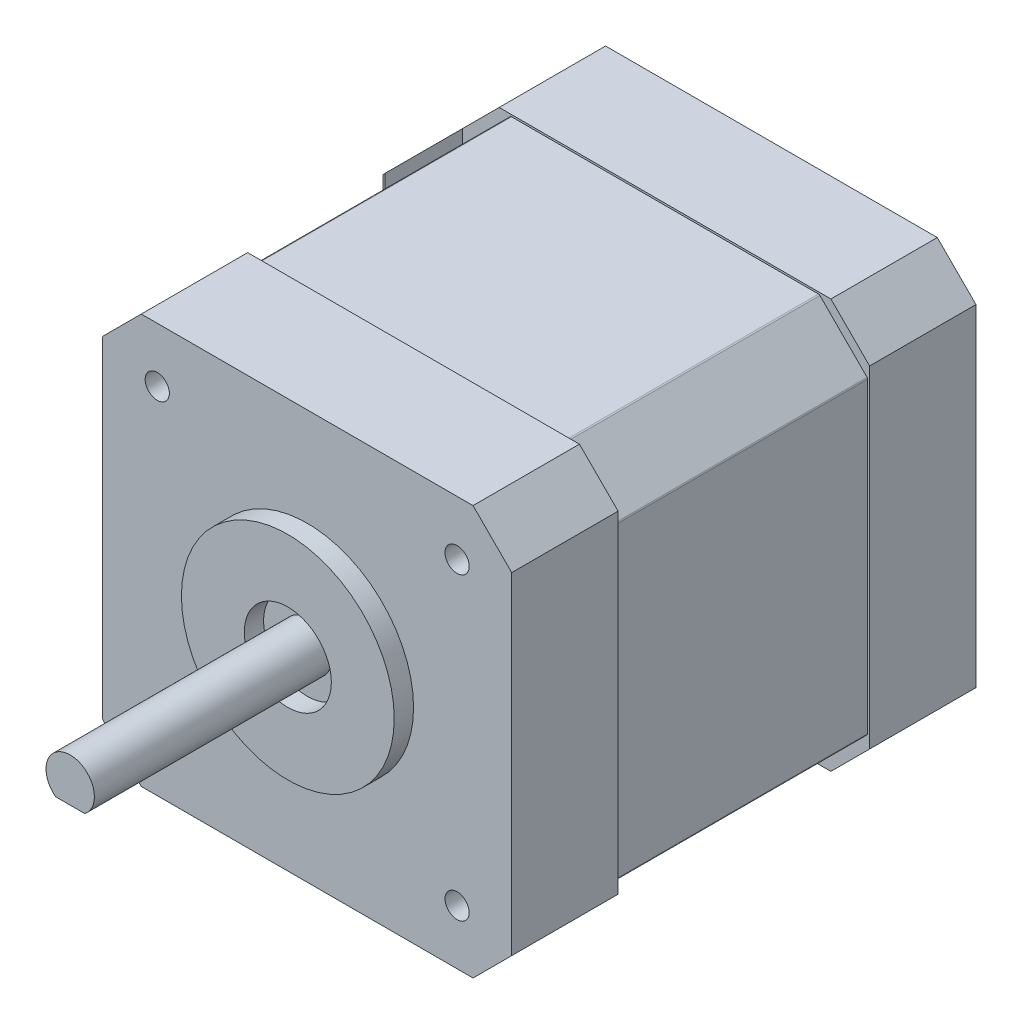
SolidWorks part; units mm, degrees
ref_plane "Plan de face" through (0, 0, 0) normal (0, 0, 1) x (1, 0, 0)
ref_plane "Plan de dessus" through (0, 0, 0) normal (0, 1, 0) x (1, 0, 0)
ref_plane "Plan de droite" through (0, 0, 0) normal (1, 0, 0) x (0, 0, -1)
ref_plane "Plan1" through (0, 0, -11) normal (0, 0, 1) x (1, 0, 0)
sketch "Esquisse1" plane through (0, 0, -11) normal (0, 0, 1) x (1, 0, 0)
  line L0 (20.95, 15.95) -> (15.95, 20.95)
  line L1 (15.95, 20.95) -> (-15.95, 20.95)
  line L2 (-15.95, 20.95) -> (-20.95, 15.95)
  line L3 (-20.95, 15.95) -> (-20.95, -15.95)
  line L4 (-20.95, -15.95) -> (-15.95, -20.95)
  line L5 (-15.95, -20.95) -> (15.95, -20.95)
  line L6 (15.95, -20.95) -> (20.95, -15.95)
  line L7 (20.95, -15.95) -> (20.95, 15.95)
extrude "Boss.-Extru.1" add sketch "Esquisse1" against normal blind 26
sketch "Esquisse2" plane through (0, 0, -37) normal (0, 0, -1) x (-1, 0, 0)
  line L0 (20.95, 21.15) -> (20.95, -21.15)
  line L1 (20.95, -21.15) -> (-21.15, -21.15)
  line L2 (-21.15, -21.15) -> (-21.15, 21.15)
  line L3 (-21.15, 21.15) -> (20.95, 21.15)
extrude "Boss.-Extru.2" add sketch "Esquisse2" along normal blind 11
sketch "Esquisse3" plane through (-20.95, 0, 0) normal (-1, 0, 0) x (0, 0, 1)
  line L0 (-40, -21.15) -> (-40, 21.15)
  line L1 (-40, 21.15) -> (-29, 21.15)
  line L2 (-29, 21.15) -> (-29, -21.15)
  line L3 (-29, -21.15) -> (-40, -21.15)
extrude "Boss.-Extru.3" add sketch "Esquisse3" along normal blind 0.2
ref_plane "Plan2" through (0, 0, -11) normal (0, 0, -1) x (-1, 0, 0)
sketch "Esquisse4" plane through (0, 0, -11) normal (0, 0, -1) x (-1, 0, 0)
  line L0 (-21.15, 21.15) -> (-21.15, -21.15)
  line L1 (-21.15, -21.15) -> (21.15, -21.15)
  line L2 (21.15, -21.15) -> (21.15, 21.15)
  line L3 (21.15, 21.15) -> (-21.15, 21.15)
extrude "Boss.-Extru.4" add sketch "Esquisse4" against normal blind 11
sketch "Esquisse5" plane through (0, 0, 0) normal (0, 0, 1) x (1, 0, 0)
  circle A0 centre (0, 0) radius 11
extrude "Boss.-Extru.5" add sketch "Esquisse5" along normal blind 2
hole_wizard "Diamètre du perçage Ø9.0 (9)1" positions "Esquisse7" profile "Esquisse6" hole size "Ø9.0" standard "Ansi Metric"
sketch "Esquisse7" plane through (0, 0, 2) normal (0, 0, 1) x (1, 0, 0)
  point P0 (0, 0)
sketch "Esquisse6" plane through (0, 0, 2) normal (1, 0, 0) x (0, -1, 0)
  line L0 (0, 0) -> (0, 2)
  line L1 (0, 2) -> (4.5, 2)
  line L2 (4.5, 2) -> (4.5, 0)
  line L5 (4.5, 0) -> (0, 0)
  line L10 (0, 2) -> (-4.5, 2) construction
  line L11 (0, -6.35) -> (0, 107.95) construction
  dimension "Diamètre du perçage" = 9
  dimension "Profondeur du perçage" = 2
  dimension "Angle de pointe" = 180
sketch "Esquisse8" plane through (0, 0, 0) normal (0, 0, 1) x (1, 0, 0)
  circle A0 centre (0, 0) radius 2.5
extrude "Boss.-Extru.6" add sketch "Esquisse8" along normal blind 24.5
sketch "Esquisse9" plane through (0, 0, 24.5) normal (0, 0, 1) x (1, 0, 0)
  line L0 (1.5, -2) -> (-1.5, -2)
  arc A0 (-1.5, -2) -> (1.5, -2) centre (0, 0) ccw
extrude "Enlèv. mat.-Extru.1" cut sketch "Esquisse9" against normal blind 15
hole_wizard "Diamètre du perçage Ø2.5 (2.5)1" positions "Esquisse11" profile "Esquisse10" hole size "Ø2.5" standard "Ansi Metric"
sketch "Esquisse11" plane through (0, 0, 0) normal (0, 0, 1) x (1, 0, 0)
  point P0 (-15.5, 15.5)
  point P1 (-15.5, -15.5)
  point P2 (15.5, -15.5)
  point P3 (15.5, 15.5)
sketch "Esquisse10" plane through (-15.5, 15.5, 0) normal (1, 0, 0) x (0, -1, 0)
  line L0 (0, 0) -> (0, 8.2511)
  line L1 (0, 8.2511) -> (1.25, 7.5)
  line L2 (1.25, 7.5) -> (1.25, 0)
  line L5 (1.25, 0) -> (0, 0)
  line L10 (0, 8.2511) -> (-1.25, 7.5) construction
  line L11 (0, -6.35) -> (0, 107.95) construction
  dimension "Diamètre du perçage" = 2.5
  dimension "Profondeur du perçage" = 7.5
  dimension "Angle de pointe" = 118
hole_wizard "Diamètre du perçage Ø4.0 (4)1" positions "Esquisse13" profile "Esquisse12" hole size "Ø4.0" standard "Ansi Metric"
sketch "Esquisse13" plane through (0, 0, -48) normal (0, 0, -1) x (-1, 0, 0)
  point P0 (-15.5, -15.5)
  point P1 (-15.5, 15.5)
  point P2 (15.5, 15.5)
  point P3 (15.5, -15.5)
sketch "Esquisse12" plane through (15.5, -15.5, -48) normal (1, 0, 0) x (0, 1, 0)
  line L0 (0, 0) -> (0, 2)
  line L1 (0, 2) -> (2, 2)
  line L2 (2, 2) -> (2, 0)
  line L5 (2, 0) -> (0, 0)
  line L10 (0, 2) -> (-2, 2) construction
  line L11 (0, -6.35) -> (0, 107.95) construction
  dimension "Diamètre du perçage" = 4
  dimension "Profondeur du perçage" = 2
  dimension "Angle de pointe" = 180
hole_wizard "Diamètre du perçage Ø10.0 (10)1" positions "Esquisse15" profile "Esquisse14" hole size "Ø10.0" standard "Ansi Metric"
sketch "Esquisse15" plane through (0, 0, -48) normal (0, 0, -1) x (-1, 0, 0)
  point P0 (0, 0)
sketch "Esquisse14" plane through (0, 0, -48) normal (1, 0, 0) x (0, 1, 0)
  line L0 (0, 0) -> (0, 2)
  line L1 (0, 2) -> (5, 2)
  line L2 (5, 2) -> (5, 0)
  line L5 (5, 0) -> (0, 0)
  line L10 (0, 2) -> (-5, 2) construction
  line L11 (0, -6.35) -> (0, 107.95) construction
  dimension "Diamètre du perçage" = 10
  dimension "Profondeur du perçage" = 2
  dimension "Angle de pointe" = 180
chamfer "Chanfrein1" distance 4 angle 45 8 edges at (21.15, 21.15, -42.5) (-21.15, -21.15, -34.5) (21.15, -21.15, -42.5) (-21.15, 21.15, -5.5) (-21.15, -21.15, -5.5) (21.15, -21.15, -5.5) (-21.15, 21.15, -34.5) (21.15, 21.15, -5.5)
fillet "Congé1" radius 0.2 8 edges at (-20.95, 15.95, -20) (-15.95, -20.95, -24) (15.95, -20.95, -24) (-15.95, 20.95, -24) (-20.95, -15.95, -20) (20.95, 15.95, -24) (20.95, -15.95, -24) (15.95, 20.95, -24)
